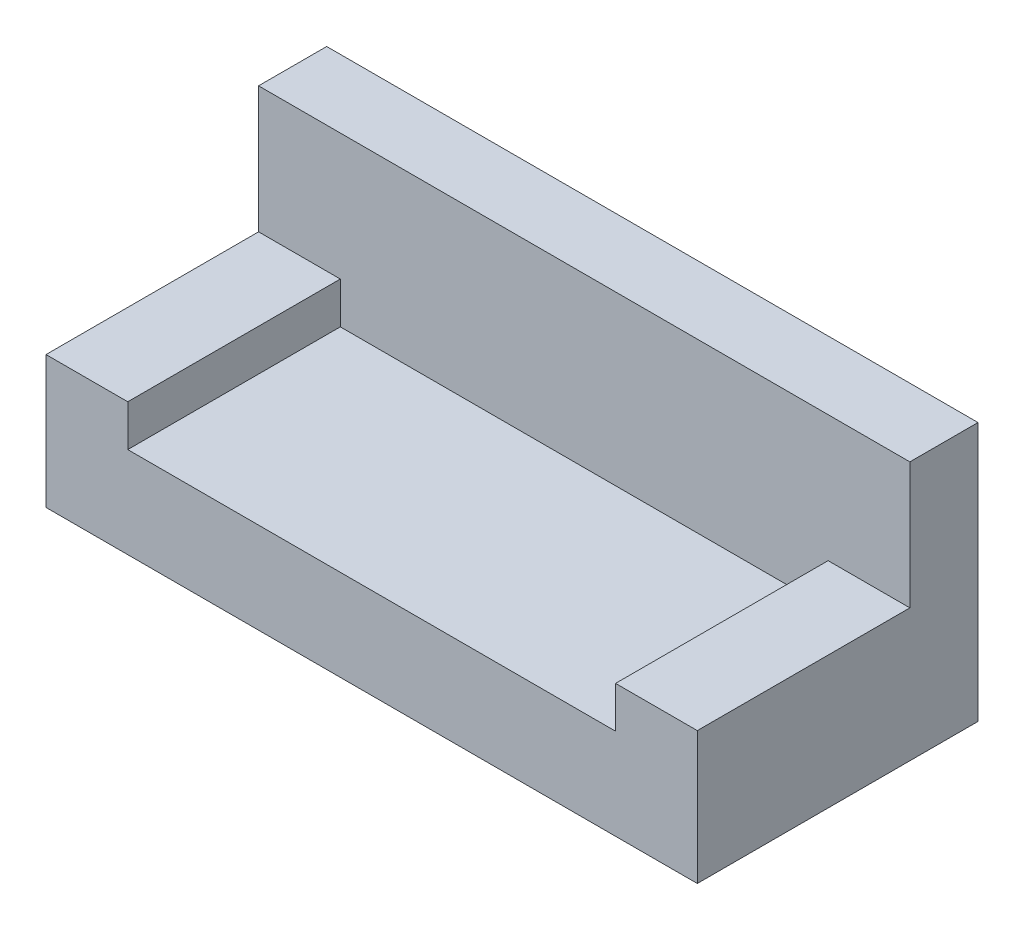
SolidWorks part; units mm, degrees
ref_plane "Спереди" through (0, 0, 0) normal (0, 0, 1) x (1, 0, 0)
ref_plane "Сверху" through (0, 0, 0) normal (0, 1, 0) x (1, 0, 0)
ref_plane "Справа" through (0, 0, 0) normal (1, 0, 0) x (0, 0, -1)
sketch "Эскиз1" plane through (0, 0, 0) normal (0, 1, 0) x (1, 0, 0)
  line L1 (0, 0) -> (2390, 0)
  line L2 (0, 0) -> (0, 1030)
  line L3 (0, 1030) -> (2390, 1030)
  line L4 (2390, 0) -> (2390, 1030)
  dimension "D1" = 2390
  dimension "D2" = 1030
extrude "Бобышка-Вытянуть1" add sketch "Эскиз1" along normal blind 950
sketch "Эскиз2" plane through (0, 950, 0) normal (0, 1, 0) x (1, 0, 0)
  line L0 (0, 0) -> (2390, 0) construction
  line L1 (300, 0) -> (2090, 0)
  line L2 (300, 0) -> (300, 780)
  line L3 (300, 780) -> (2090, 780)
  line L4 (2090, 0) -> (2090, 780)
  line L5 (300, 780) -> (0, 780) construction
  line L6 (0, 1030) -> (0, 0) construction
  line L7 (2090, 780) -> (2390, 780) construction
  line L8 (2390, 0) -> (2390, 1030) construction
  line L9 (2390, 1030) -> (0, 1030) construction
  dimension "D1" = 250
  dimension "D2" = 300
extrude "Вырез-Вытянуть1" cut sketch "Эскиз2" against normal blind 616
sketch "Эскиз3" plane through (0, 950, 0) normal (0, 1, 0) x (1, 0, 0)
  line L1 (0, 0) -> (300, 0)
  line L2 (0, 0) -> (0, 780)
  line L3 (0, 780) -> (300, 780)
  line L4 (300, 0) -> (300, 780)
  line L5 (2390, 0) -> (2090, 0)
  line L6 (2390, 0) -> (2390, 780)
  line L7 (2390, 780) -> (2090, 780)
  line L8 (2090, 0) -> (2090, 780)
extrude "Вырез-Вытянуть2" cut sketch "Эскиз3" against normal blind 464
